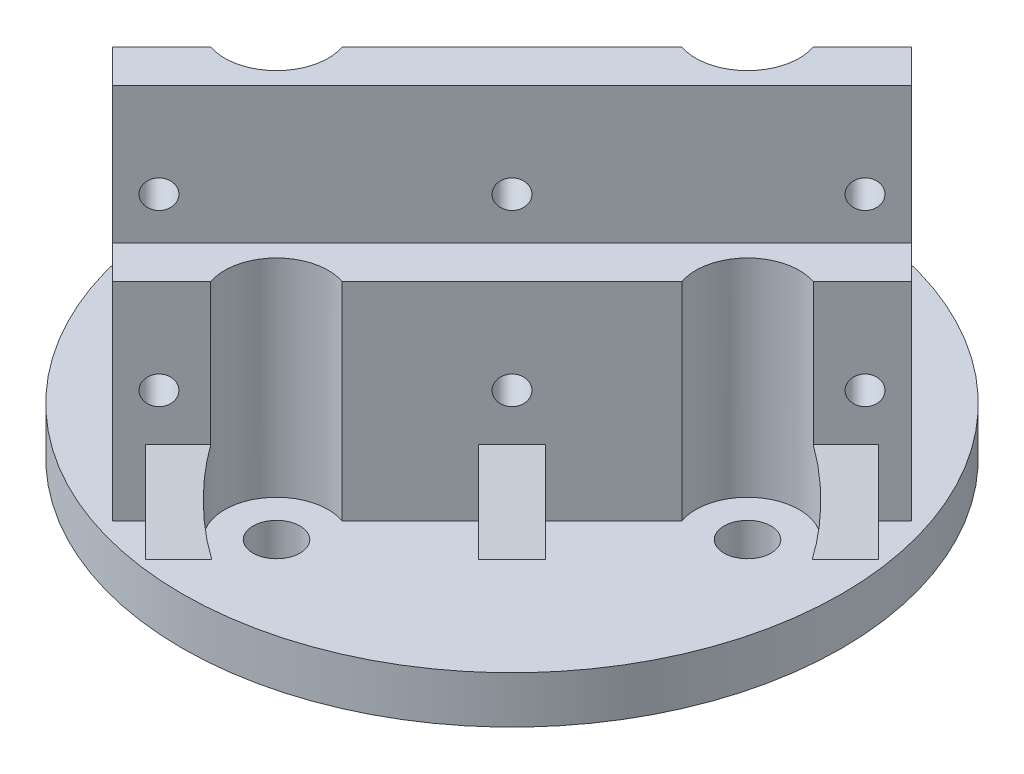
SolidWorks part; units mm, degrees
ref_plane "前基準面" through (0, 0, 0) normal (0, 0, 1) x (1, 0, 0)
ref_plane "上基準面" through (0, 0, 0) normal (0, 1, 0) x (1, 0, 0)
ref_plane "右基準面" through (0, 0, 0) normal (1, 0, 0) x (0, 0, -1)
sketch "草圖1" plane through (0, 0, 0) normal (0, 1, 0) x (1, 0, 0)
  line L0 (-35, 0) -> (35, 0) construction
  line L1 (0, 35) -> (0, -35) construction
  circle A0 centre (0, 0) radius 35
  circle A1 centre (0, 0) radius 25 construction
  circle A2 centre (0, 25) radius 2.5
  circle A3 centre (25, 0) radius 2.5
  circle A4 centre (0, -25) radius 2.5
  circle A5 centre (-25, 0) radius 2.5
  point P16 (0, 36.889)
  point P17 (37.5579, 0)
  dimension "D1" = 5
  dimension "D2" = 50
  dimension "D3" = 70
extrude "填料-伸長1" add sketch "草圖1" along normal blind 5
sketch "草圖2" plane through (0, 5, 0) normal (0, 1, 0) x (1, 0, 0)
  line L0 (-24.7487, -24.7487) -> (24.7487, 24.7487) construction
  line L1 (-25, 0) -> (0, -25) construction
  circle A0 centre (0, 0) radius 35 construction
ref_plane "平面1" through (0, 0, 0) normal (0.7071, 0, -0.7071) x (-0.7071, 0, -0.7071)
sketch "草圖3" plane through (0, 0, 0) normal (0.7071, 0, -0.7071) x (-0.7071, 0, -0.7071)
  line L0 (0, 0) -> (0, 27) construction
  line L1 (15.25, 5) -> (-15.25, 5)
  line L2 (15.25, 5) -> (15.25, 27)
  line L3 (15.25, 27) -> (10.25, 27)
  line L4 (-15.25, 5) -> (-15.25, 27)
  line L6 (10.25, 27) -> (10.25, 7)
  line L7 (10.25, 7) -> (-10.25, 7)
  line L8 (-10.25, 27) -> (-10.25, 7)
  line L9 (-10.25, 27) -> (-15.25, 27)
  line L10 (-15.1777, 5) -> (-20.1777, 5) construction
  point P9 (0, 5)
  point P14 (0, 7)
  point P15 (0, 28.1551)
  point P16 (0, 0)
  point P17 (0, 26.9336)
  point P18 (0, 0)
  point P19 (0, 0)
  point P20 (0, 0)
  point P21 (0, 0)
  dimension "D1" = 20
  dimension "D2" = 20.5
  dimension "D3" = 2
  dimension "D4" = 5
extrude "填料-伸長2" add sketch "草圖3" along normal mid plane 60
sketch "草圖4" plane through (0, 0, 0) normal (0.7071, 0, -0.7071) x (-0.7071, 0, -0.7071)
  line L0 (-15.25, 12) -> (-15.25, 5)
  line L1 (-15.25, 27) -> (-15.25, 5) construction
  line L2 (-15.25, 5) -> (-20.25, 5)
  line L3 (-15.25, 5) -> (-20.1777, 5) construction
  line L4 (-20.25, 5) -> (-15.25, 12)
  dimension "D1" = 7
  dimension "D2" = 5
extrude "填料-伸長3" add sketch "草圖4" along normal mid plane 5
pattern_linear "直線複製排列1" count 2 spacing 25 along (-0.7071, 0, 0.7071) count 2 spacing 25 along (0.7071, 0, -0.7071) of "填料-伸長3"
ref_plane "平面2" through (0, 0, 0) normal (0.7071, 0, 0.7071) x (0.7071, 0, -0.7071)
mirror "鏡射1" about plane through (0, 0, 0) normal (0.7071, 0, 0.7071) of "直線複製排列1", "填料-伸長3"
sketch "草圖5" plane through (0, 5, 0) normal (0, 1, 0) x (1, 0, 0)
  circle A0 centre (0, 25) radius 5.5
  circle A1 centre (-25, 0) radius 5.5
  circle A2 centre (0, -25) radius 5.5
  circle A3 centre (25, 0) radius 5.5
  dimension "D1" = 11
extrude "除料-伸長1" cut sketch "草圖5" along normal up to surface (22 mm away) up to face at (-9.0156, 27, -9.0156)
sketch "草圖6" plane through (-10.7834, 0, -10.7834) normal (-0.7071, 0, -0.7071) x (-0.7071, 0, 0.7071)
  line L0 (-30, 17) -> (30, 17) construction
  line L1 (-30, 5) -> (-30, 27) construction
  line L2 (30, 5) -> (30, 27) construction
  line L3 (-30, 27) -> (-22.6129, 27) construction
  circle A0 centre (0, 17) radius 1.5
  circle A1 centre (-26.5, 17) radius 1.5
  circle A2 centre (26.5, 17) radius 1.5
  dimension "D2" = 3
  dimension "D1" = 10
  dimension "D3" = 3.5
  dimension "D4" = 3.5
extrude "除料-伸長2" cut sketch "草圖6" against normal through all
